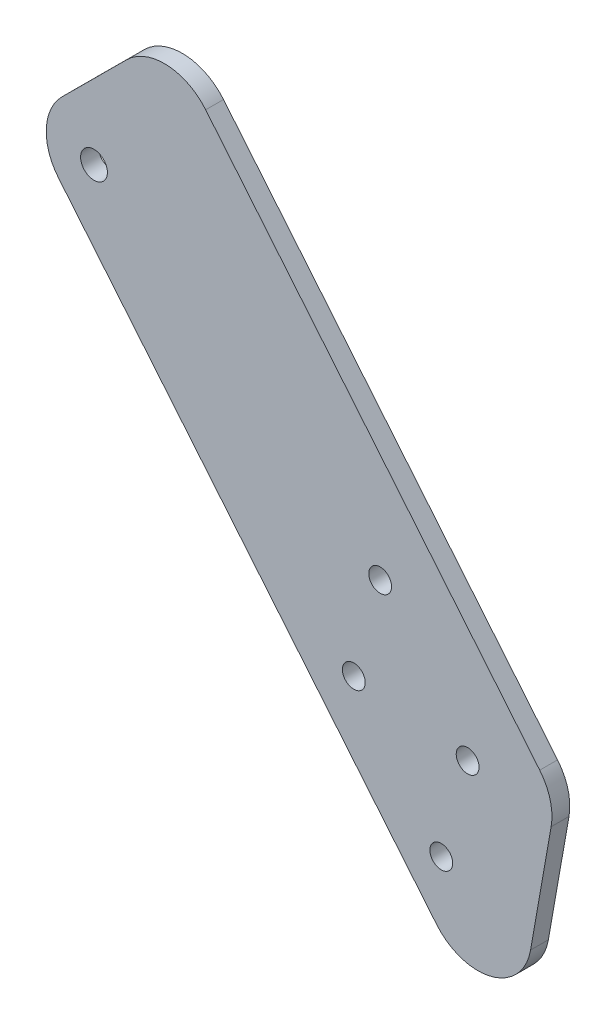
SolidWorks part; units mm, degrees
ref_plane "Front Plane" through (0, 0, 0) normal (0, 0, 1) x (1, 0, 0)
ref_plane "Top Plane" through (0, 0, 0) normal (0, 1, 0) x (1, 0, 0)
ref_plane "Right Plane" through (0, 0, 0) normal (1, 0, 0) x (0, 0, -1)
sketch "Sketch1" plane through (0, 0, 0) normal (0, 0, 1) x (1, 0, 0)
  line L0 (-13.5496, 51.2012) -> (55.396, -32.3587)
  line L1 (55.396, -32.3587) -> (47.3996, -77.8659)
  line L2 (40.2485, -74.7853) -> (44.914, -76.7951) construction
  line L3 (-13.5496, 51.2012) -> (-38.6358, 26.209)
  line L4 (-49.8487, 29.7064) -> (-8.2354, 16.7267) construction
  line L5 (-38.6358, 26.209) -> (47.3996, -77.8659)
  arc A0 (55.3317, -34.7786) -> (54.333, -30.1838) centre (50.4319, -33.4377) ccw construction
  circle A1 centre (-26.7808, 24.7075) radius 2.39 construction
  circle A2 centre (24.1867, -13.8684) radius 2.032 construction
  circle A3 centre (19.4933, -31.0178) radius 2.032 construction
  circle A4 centre (39.7631, -33.9317) radius 2.032 construction
  circle A5 centre (35.0697, -51.0811) radius 2.032 construction
  circle A6 centre (-26.7808, 24.7075) radius 2.39
  circle A7 centre (24.1867, -13.8684) radius 2.032
  circle A8 centre (19.4933, -31.0178) radius 2.032
  circle A9 centre (39.7631, -33.9317) radius 2.032
  circle A10 centre (35.0697, -51.0811) radius 2.032
extrude "Boss-Extrude1" add sketch "Sketch1" along normal blind 3.175
fillet "Fillet1" radius 9.525 4 edges at (47.3996, -77.8659, 1.5875) (55.396, -32.3587, 1.5875) (-13.5496, 51.2012, 1.5875) (-38.6358, 26.209, 1.5875)
